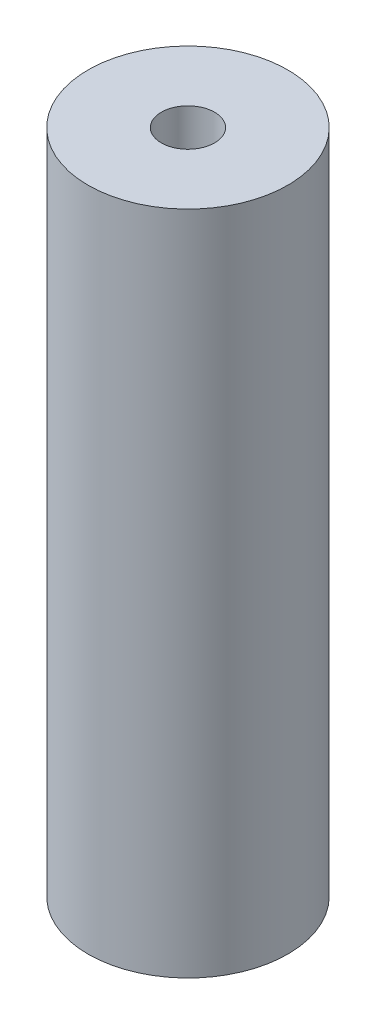
SolidWorks part; units mm, degrees
material "5052-H34"
ref_plane "正面" through (0, 0, 0) normal (0, 0, 1) x (1, 0, 0)
ref_plane "平面" through (0, 0, 0) normal (0, 1, 0) x (1, 0, 0)
ref_plane "右側面" through (0, 0, 0) normal (1, 0, 0) x (0, 0, -1)
sketch "ｽｹｯﾁ1" plane through (0, 0, 0) normal (0, 1, 0) x (1, 0, 0)
  circle A0 centre (0, 0) radius 7.5
  circle A1 centre (0, 0) radius 2
  dimension "D1" = 4
  dimension "D2" = 15
extrude "ﾎﾞｽ - 押し出し1" add sketch "ｽｹｯﾁ1" along normal blind 50
